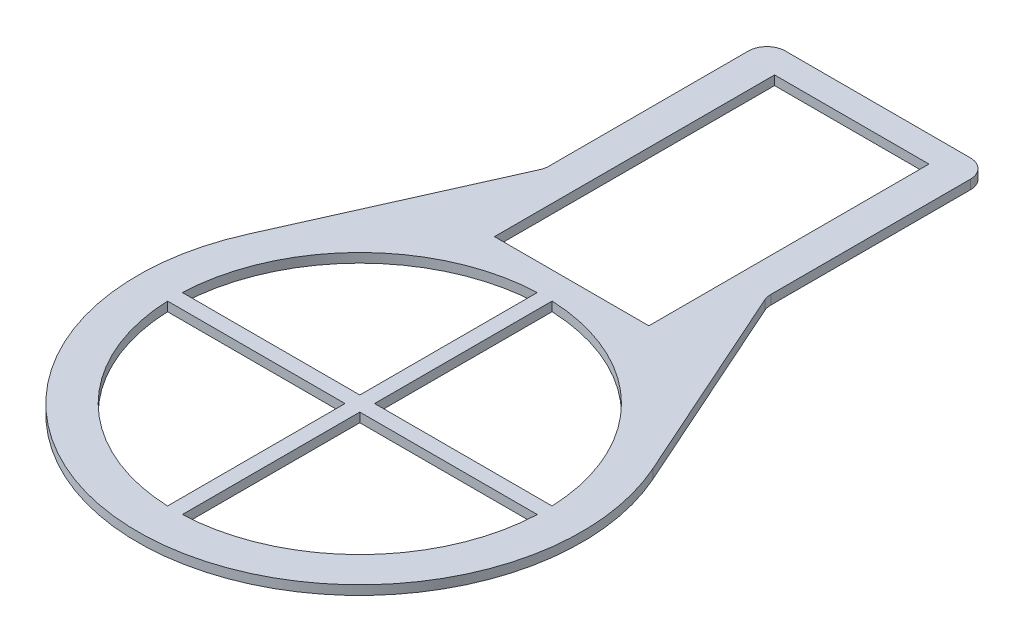
SolidWorks part; units mm, degrees
ref_plane "Front Plane" through (0, 0, 0) normal (0, 0, 1) x (1, 0, 0)
ref_plane "Top Plane" through (0, 0, 0) normal (0, 1, 0) x (1, 0, 0)
ref_plane "Right Plane" through (0, 0, 0) normal (1, 0, 0) x (0, 0, -1)
sketch "Sketch1" plane through (0, 0, 0) normal (0, 1, 0) x (1, 0, 0)
  line L1 (-38.1, 101.6) -> (-69.5843, 31.0559)
  line L2 (-38.1, 177.8) -> (38.1, 177.8)
  line L3 (-38.1, 177.8) -> (-38.1, 101.6)
  line L4 (-38.1, 101.6) -> (38.1, 101.6)
  line L5 (38.1, 177.8) -> (38.1, 101.6)
  line L6 (-38.1, 177.8) -> (38.1, 101.6) construction
  line L7 (-38.1, 101.6) -> (38.1, 177.8) construction
  line L8 (38.1, 101.6) -> (69.5843, 31.0559)
  circle A0 centre (0, 0) radius 76.2
  point P4 (0, 139.7)
  dimension "D1" = 152.4
  dimension "D2" = 76.2
  dimension "D3" = 76.2
  dimension "D4" = 139.7
extrude "Boss-Extrude1" add sketch "Sketch1" along normal blind 3.175 contours A0 | A0 L8 L4 L1 | L5 L2 L3 L4
fillet "Fillet1" radius 6.35 4 edges at (-38.1, 1.5875, -101.6) (-38.1, 1.5875, -177.8) (38.1, 1.5875, -101.6) (38.1, 1.5875, -177.8)
sketch "Sketch2" plane through (0, 3.175, 0) normal (0, 1, 0) x (1, 0, 0)
  line L0 (0, 0) -> (-63.5, 0)
  line L1 (0, 0) -> (63.5, 0)
  line L2 (0, 0) -> (0, 63.5)
  line L3 (0, 0) -> (0, -63.5)
  line L4 (2.54, 0) -> (2.54, 63.5)
  line L5 (0, -2.54) -> (63.5, -2.54)
  line L6 (-2.54, 0) -> (-2.54, -63.5)
  line L7 (0, 2.54) -> (-63.5, 2.54)
  line L8 (-2.54, 0) -> (-2.54, 63.5)
  line L9 (0, 2.54) -> (63.5, 2.54)
  line L10 (2.54, 0) -> (2.54, -63.5)
  line L11 (0, -2.54) -> (-63.5, -2.54)
  circle A0 centre (0, 0) radius 63.5
  dimension "D1" = 127
  dimension "D2" = 2.54
  dimension "D3" = 2.54
extrude "Cut-Extrude1" cut sketch "Sketch2" against normal blind 3.175 contours L8 A0 L7 | L9 A0 L4 | L10 A0 L5 | L11 A0 L6
sketch "Sketch3" plane through (0, 3.175, 0) normal (0, 1, 0) x (1, 0, 0)
  line L1 (-26.4948, 72.7091) -> (26.4948, 72.7091)
  line L2 (-26.4948, 72.7091) -> (-26.4948, 168.8375)
  line L3 (-26.4948, 168.8375) -> (26.4948, 168.8375)
  line L4 (26.4948, 72.7091) -> (26.4948, 168.8375)
  line L5 (-26.4948, 72.7091) -> (26.4948, 168.8375) construction
  line L6 (-26.4948, 168.8375) -> (26.4948, 72.7091) construction
  point P0 (0, 120.7733)
extrude "Cut-Extrude2" cut sketch "Sketch3" against normal blind 3.175
